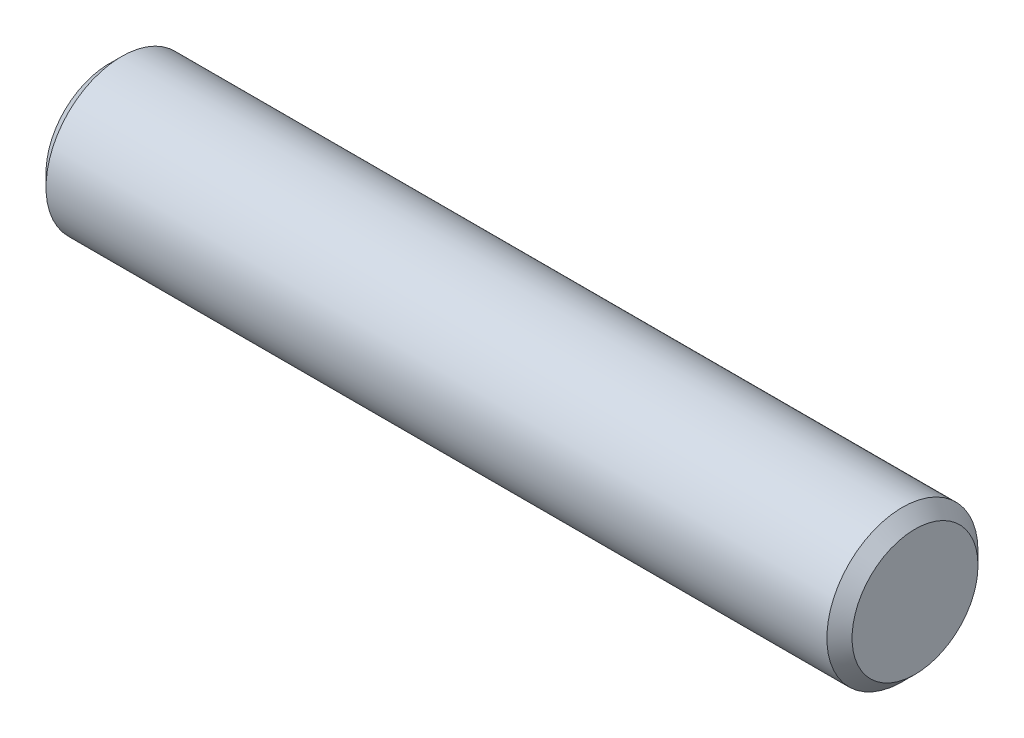
SolidWorks part; units mm, degrees
material "Oak"
ref_plane "Front" through (0, 0, 0) normal (0, 0, 1) x (1, 0, 0)
ref_plane "Top" through (0, 0, 0) normal (0, 1, 0) x (1, 0, 0)
ref_plane "Right" through (0, 0, 0) normal (1, 0, 0) x (0, 0, -1)
sketch "Sketch2" plane through (0, 0, 0) normal (1, 0, 0) x (0, 0, -1)
  circle A0 centre (0, 0) radius 3
  dimension "D1" = 6
extrude "Boss-Extrude1" add sketch "Sketch2" along normal mid plane 32
chamfer "Chamfer1" distance 0.5 angle 45 2 edges at (-16, 0, -3) (16, 0, -3)
